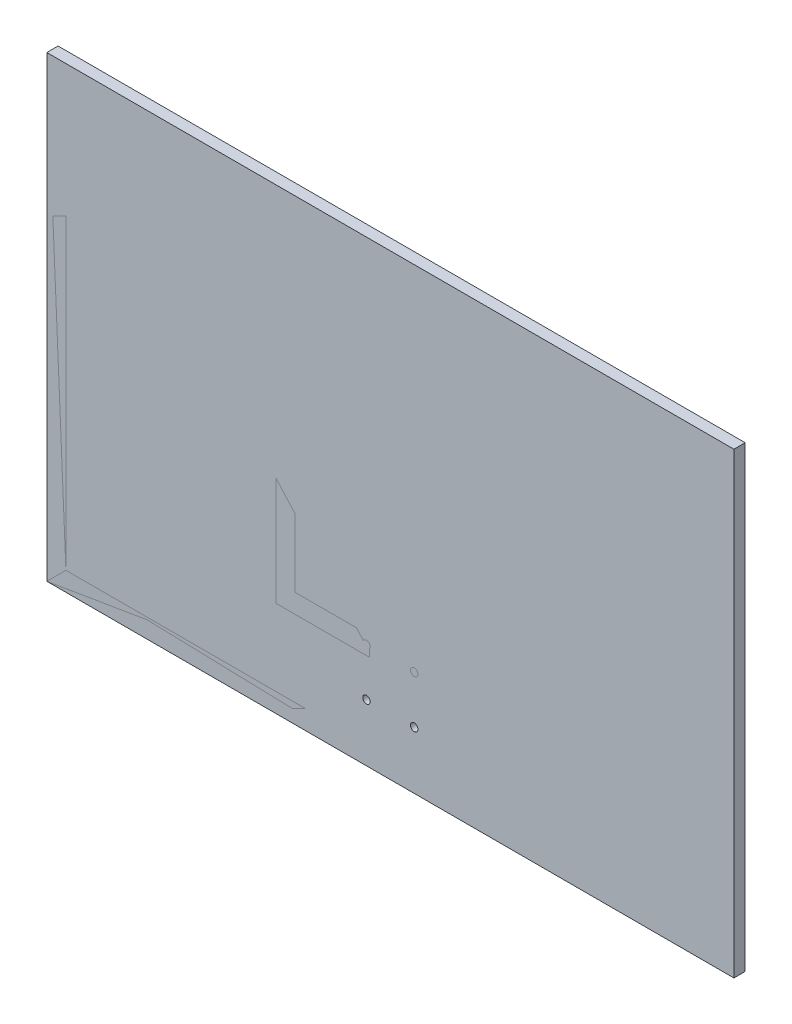
SolidWorks part; units mm, degrees
material "Acrylic (Medium-high impact)"
ref_plane "Front Plane" through (0, 0, 0) normal (0, 0, 1) x (1, 0, 0)
ref_plane "Top Plane" through (0, 0, 0) normal (0, 1, 0) x (1, 0, 0)
ref_plane "Right Plane" through (0, 0, 0) normal (1, 0, 0) x (0, 0, -1)
sketch "Sketch1" plane through (0, 0, 0) normal (1, 0, 0) x (0, 0, -1)
  line L1 (0, 0) -> (-30, 0)
  line L2 (0, 0) -> (0, 1219)
  line L3 (0, 1219) -> (-30, 1219)
  line L4 (-30, 0) -> (-30, 1219)
  dimension "D2" = 30
  dimension "D1" = 1219
extrude "Boss-Extrude5" add sketch "Sketch1" against normal blind 1829
sketch "Sketch4" plane through (0, 0, 30) normal (0, 0, 1) x (1, 0, 0)
  line L0 (-914.5, 1219) -> (-914.5, 0) construction
  line L1 (-1829, 1219) -> (0, 1219)
  line L2 (-1829, 1219) -> (-1829, 0)
  line L3 (-1829, 0) -> (0, 0)
  line L4 (0, 1219) -> (0, 0)
  line L5 (-1778.2, 1168.2) -> (-50.8, 1168.2)
  line L6 (-1778.2, 1168.2) -> (-1778.2, 50.8)
  line L7 (-1778.2, 50.8) -> (-50.8, 50.8)
  line L8 (-50.8, 1168.2) -> (-50.8, 50.8)
  line L9 (-1829, 609.5) -> (0, 609.5) construction
  point P14 (-914.5, 1168.2)
  point P15 (-1778.2, 609.5)
  dimension "D1" = 50.8
  dimension "D2" = 50.8
surface "Surface-Plane1" sketch "Sketch4"
sketch "Sketch5" plane through (0, 0, 30) normal (0, 0, 1) x (1, 0, 0)
  line L0 (-914.5, 1219) -> (-914.5, 0) construction
  line L1 (0, 1219) -> (-1829, 1219) construction
  line L2 (-1829, 0) -> (0, 0) construction
  line L3 (-1829, 609.5) -> (0, 609.5) construction
  line L4 (-1829, 1219) -> (-1829, 0) construction
  line L5 (0, 0) -> (0, 1219) construction
  line L7 (-1219.3, 254.2) -> (-609.7, 254.2)
  line L8 (-1219.3, 254.2) -> (-1219.3, 711.4)
  line L9 (-1219.3, 711.4) -> (-609.7, 711.4)
  line L10 (-609.7, 254.2) -> (-609.7, 711.4)
  line L11 (-1219.3, 254.2) -> (-609.7, 711.4) construction
  line L12 (-1219.3, 711.4) -> (-609.7, 254.2) construction
  line L13 (-1168.5, 660.6) -> (-660.5, 660.6)
  line L14 (-1168.5, 660.6) -> (-1168.5, 305)
  line L15 (-1168.5, 305) -> (-660.5, 305)
  line L16 (-660.5, 660.6) -> (-660.5, 305)
  point P12 (-914.5, 482.8)
  point P17 (-914.5, 711.4)
  point P22 (-914.5, 660.6)
  dimension "D1" = 609.6
  dimension "D2" = 457.2
  dimension "D4" = 50.8
  dimension "D5" = 50.8
  dimension "D6" = 50.8
  dimension "D3" = 305
surface "Surface-Plane2" sketch "Sketch5"
sketch "Sketch6" plane through (0, 0, 30) normal (0, 0, 1) x (1, 0, 0)
  line L0 (-914.5, 0) -> (-914.5, 1219) construction
  line L1 (-978, 279.6) -> (-851, 279.6) construction
  line L2 (-978, 279.6) -> (-978, 152.6) construction
  line L3 (-978, 152.6) -> (-851, 152.6) construction
  line L4 (-851, 279.6) -> (-851, 152.6) construction
  line L5 (-1829, 0) -> (0, 0) construction
  line L6 (0, 1219) -> (-1829, 1219) construction
  line L7 (-1829, 279.6) -> (0, 279.6) construction
  line L8 (-1829, 1219) -> (-1829, 0) construction
  line L9 (0, 0) -> (0, 1219) construction
  line L10 (-978, 216.1) -> (-851, 216.1) construction
  circle A0 centre (-978, 279.6) radius 10
  circle A1 centre (-851, 279.6) radius 10
  circle A2 centre (-851, 152.6) radius 10
  circle A3 centre (-978, 152.6) radius 10
  point P10 (-914.5, 279.6)
  dimension "D3" = 20
  dimension "D1" = 127
  dimension "D2" = 279.6
extrude "Cut-Extrude1" cut sketch "Sketch6" against normal through all
equation "\"Backboard Width\"= 182.9"
equation "\"Backboard Height\"= 121.9"
equation "\"Backboard Thickness\"= 3"
equation "\"D2@Sketch1\"=\"Backboard Thickness\""
equation "\"Backboard Cosmetic Rectangle Thickness\"= 5.08"
equation "\"D1@Sketch1\"=\"Backboard Height\""
equation "\"D1@Boss-Extrude5\"=\"Backboard Width\""
equation "\"D1@Sketch4\"=\"Backboard Cosmetic Rectangle Thickness\""
equation "\"D2@Sketch4\"=\"Backboard Cosmetic Rectangle Thickness\""
equation "\"D4@Sketch5\"=\"Backboard Cosmetic Rectangle Thickness\""
equation "\"D5@Sketch5\"=\"Backboard Cosmetic Rectangle Thickness\""
equation "\"D6@Sketch5\"=\"Backboard Cosmetic Rectangle Thickness\""
equation "\"Nail Diameter from Rim\"= 2.00cm"
equation "\"D3@Sketch6\"=\"Nail Diameter from Rim\""
